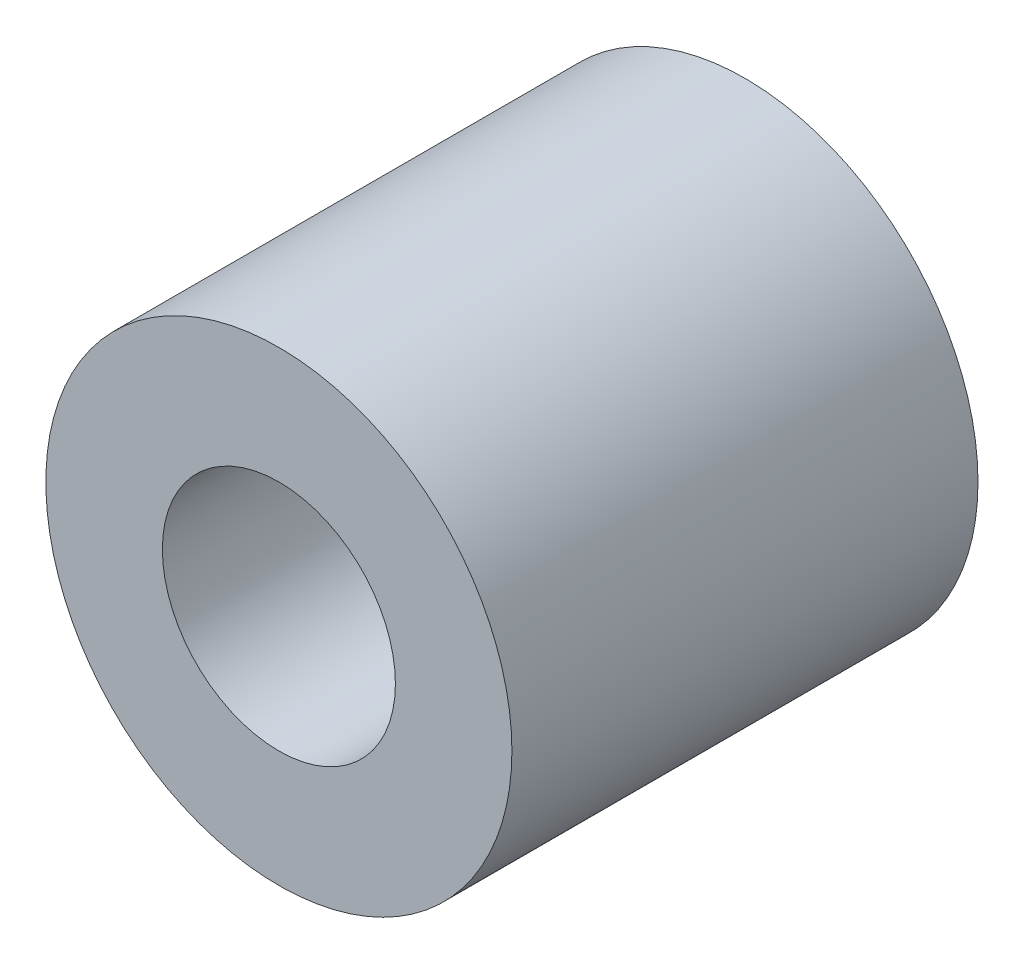
SolidWorks part; units mm, degrees
ref_plane "Front Plane" through (0, 0, 0) normal (0, 0, 1) x (1, 0, 0)
ref_plane "Top Plane" through (0, 0, 0) normal (0, 1, 0) x (1, 0, 0)
ref_plane "Right Plane" through (0, 0, 0) normal (1, 0, 0) x (0, 0, -1)
sketch "Sketch1" plane through (0, 0, 0) normal (0, 0, 1) x (1, 0, 0)
  circle A0 centre (-27.5487, 9.6114) radius 6.35
  circle A1 centre (-27.5487, 9.6114) radius 3.175
  dimension "D1" = 6.35
  dimension "D2" = 12.7
extrude "Boss-Extrude1" add sketch "Sketch1" along normal blind 12.7
